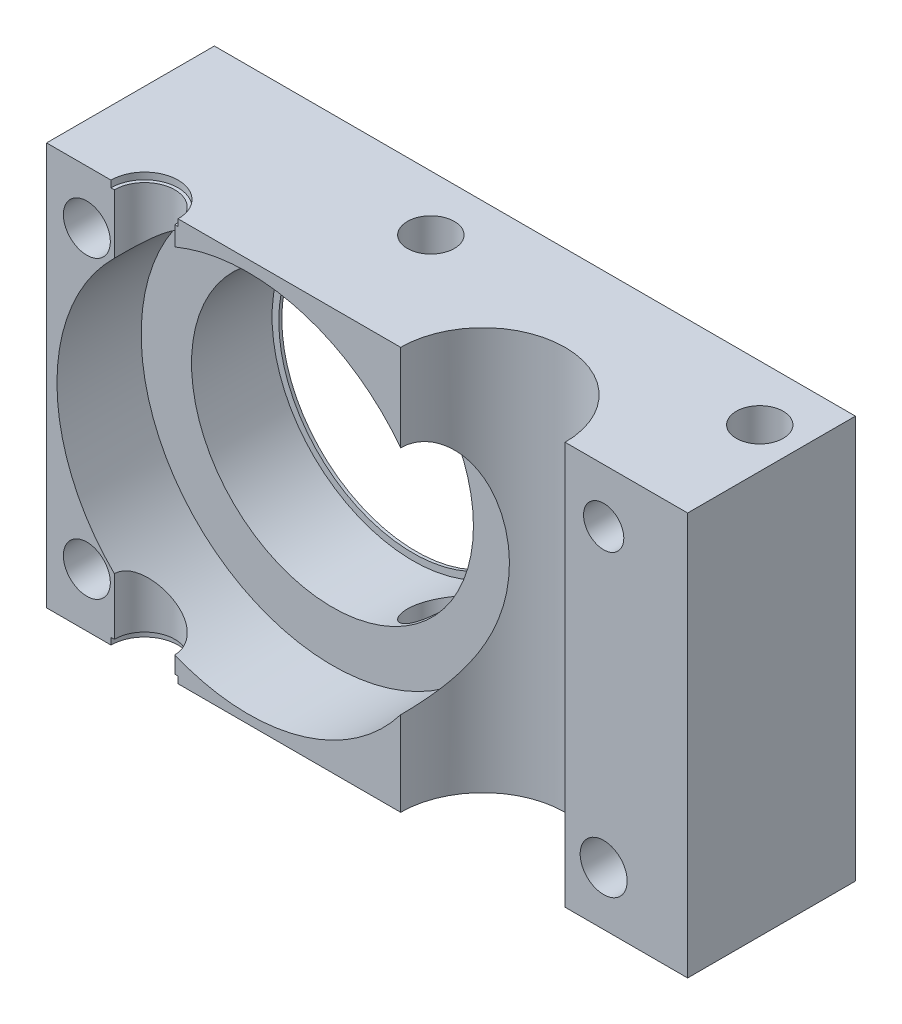
SolidWorks part; units mm, degrees
ref_plane "Front Plane" through (0, 0, 0) normal (0, 0, 1) x (1, 0, 0)
ref_plane "Top Plane" through (0, 0, 0) normal (0, 1, 0) x (1, 0, 0)
ref_plane "Right Plane" through (0, 0, 0) normal (1, 0, 0) x (0, 0, -1)
sketch "Sketch2" plane through (0, 0, 0) normal (0, 0, 1) x (1, 0, 0)
  line L0 (-172.9415, 33.7452) -> (-180.4515, 33.7452)
  line L5 (-180.4515, 33.7452) -> (-268.4515, 33.7452)
  line L7 (-172.9415, 93.7452) -> (-268.4515, 93.7452)
  line L8 (-268.4515, 33.7452) -> (-268.4515, 93.7452)
  line L12 (-172.9415, 93.7452) -> (-172.9415, 33.7452)
  point P4 (-234.7995, 64.7273)
  dimension "D1" = 88
  dimension "D2" = 60
extrude "Boss-Extrude1" add sketch "Sketch2" along normal blind 25
extrude "Cut-Extrude1" cut sketch "Sketch3" against normal blind 30 contours A4 | A2 | A3 | A5
sketch "Sketch3" plane through (-254.5268, 25.614, 25) normal (0, 0, 1) x (1, 0, 0)
  line L0 (81.5853, 68.1312) -> (-13.9247, 68.1312) construction
  line L1 (81.5853, 8.1312) -> (-13.9247, 8.1312) construction
  line L2 (-13.9247, 8.1312) -> (-13.9247, 68.1312) construction
  circle A0 centre (16.1218, 37.9418) radius 10
  circle A1 centre (16.1218, 37.9418) radius 28.5
  circle A2 centre (69.0753, 60.1312) radius 3
  circle A3 centre (69.0753, 16.1312) radius 3.5
  circle A4 centre (-7.9247, 60.1312) radius 3.5
  circle A5 centre (-7.9247, 16.1312) radius 3.5
  dimension "D1" = 8
  dimension "D7" = 7
  dimension "D8" = 6
  dimension "D2" = 8
  dimension "D3" = 8
  dimension "D4" = 8
  dimension "D5" = 6
  dimension "D6" = 6
extrude "Cut-Extrude3" cut sketch "Sketch5" against normal blind 299.5
sketch "Sketch5" plane through (-254.5268, 218.82, 46.8901) normal (0, 1, 0) x (0, 0, 1)
  circle A0 centre (-21.8901, 51.0814) radius 12.25
  dimension "D1" = 24.5
extrude "Cut-Extrude6" cut sketch "Sketch8" against normal blind 299.5
sketch "Sketch8" plane through (-254.5268, 25.614, 25) normal (0, 0, 1) x (1, 0, 0)
  circle A0 centre (16.1218, 37.9418) radius 20
  dimension "D1" = 40
extrude "Cut-Extrude5" cut sketch "Sketch7" against normal blind 12.55
sketch "Sketch7" plane through (-254.5268, 25.614, 25) normal (0, 0, 1) x (1, 0, 0)
  circle A0 centre (16.1218, 37.9418) radius 28.5
sketch "Sketch9" plane through (0, 0, 12.45) normal (0, 0, 1) x (1, 0, 0)
  circle A0 centre (-238.4049, 63.5557) radius 21
extrude "Cut-Extrude7" cut sketch "Sketch9" against normal blind 12 contours A0
fillet "Fillet1" [suppressed] radius 1
ref_plane "Plane3" through (0, 63.7452, 0) normal (0, -1, 0) x (-1, 0, 0)
extrude "Cut-Extrude11" cut sketch "Sketch18" against normal blind 70
sketch "Sketch18" plane through (-155.7534, 103.7452, -13.0138) normal (0, 1, 0) x (0, 0, 1)
  circle A2 centre (21.2638, -72.1919) radius 3.5
  circle A3 centre (21.2638, -23.1919) radius 3.5
extrude "Cut-Extrude18" cut sketch "Sketch25" against normal blind 15
sketch "Sketch25" plane through (-254.5268, 93.7452, 46.8901) normal (0, 1, 0) x (0, 0, 1)
  arc A1 (-26.8901, 0.672) -> (-16.8901, 0.672) centre (-21.8901, 0.672) ccw
  arc A3 (-16.8901, 0.672) -> (-26.8901, 0.672) centre (-21.8901, 0.672) ccw
  circle A4 centre (-21.8901, 0.672) radius 4.5
extrude "Cut-Extrude19" cut sketch "Sketch26" against normal blind 15
sketch "Sketch26" plane through (-254.5268, 33.7452, 3.1099) normal (0, -1, 0) x (0, 0, -1)
  arc A1 (-26.8901, 0.672) -> (-16.8901, 0.672) centre (-21.8901, 0.672) ccw
  arc A3 (-16.8901, 0.672) -> (-26.8901, 0.672) centre (-21.8901, 0.672) ccw
  circle A4 centre (-21.8901, 0.672) radius 4.5
extrude "Cut-Extrude22" cut sketch "Sketch29" against normal blind 2
sketch "Sketch29" plane through (-217.1634, 32.7452, 13.1375) normal (0, -1, 0) x (-1, 0, 0)
  arc A1 (36.6913, -16.8625) -> (36.6913, -6.8625) centre (36.6913, -11.8625) ccw
  arc A3 (36.6913, -6.8625) -> (36.6913, -16.8625) centre (36.6913, -11.8625) ccw
extrude "Cut-Extrude23" cut sketch "Sketch30" against normal blind 2
sketch "Sketch30" plane through (-217.1634, 94.7452, 36.8625) normal (0, 1, 0) x (-1, 0, 0)
  arc A1 (36.6913, -16.8625) -> (36.6913, -6.8625) centre (36.6913, -11.8625) ccw
  arc A3 (36.6913, -6.8625) -> (36.6913, -16.8625) centre (36.6913, -11.8625) ccw
sketch "Sketch31" plane through (0, 33.7452, 0) normal (0, -1, 0) x (1, 0, 0)
  line L0 (-253.8547, 25) -> (-268.4515, 25)
  line L1 (-203.4454, 25) -> (-253.8547, 25)
